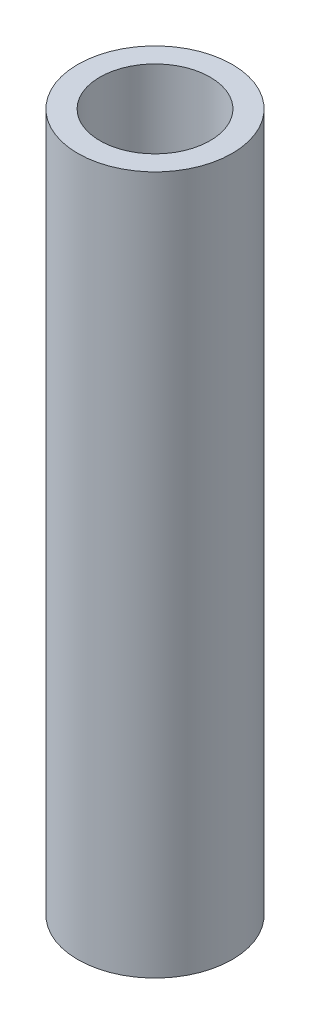
SolidWorks part; units mm, degrees
ref_plane "Front Plane" through (0, 0, 0) normal (0, 0, 1) x (1, 0, 0)
ref_plane "Top Plane" through (0, 0, 0) normal (0, 1, 0) x (1, 0, 0)
ref_plane "Right Plane" through (0, 0, 0) normal (1, 0, 0) x (0, 0, -1)
sketch "Sketch1" plane through (0, 0, 0) normal (0, 1, 0) x (1, 0, 0)
  circle A0 centre (0, 0) radius 9.525
  circle A1 centre (0, 0) radius 13.335
  dimension "D1" = 26.67
  dimension "D2" = 19.05
extrude "Boss-Extrude1" add sketch "Sketch1" along normal blind 120.65
